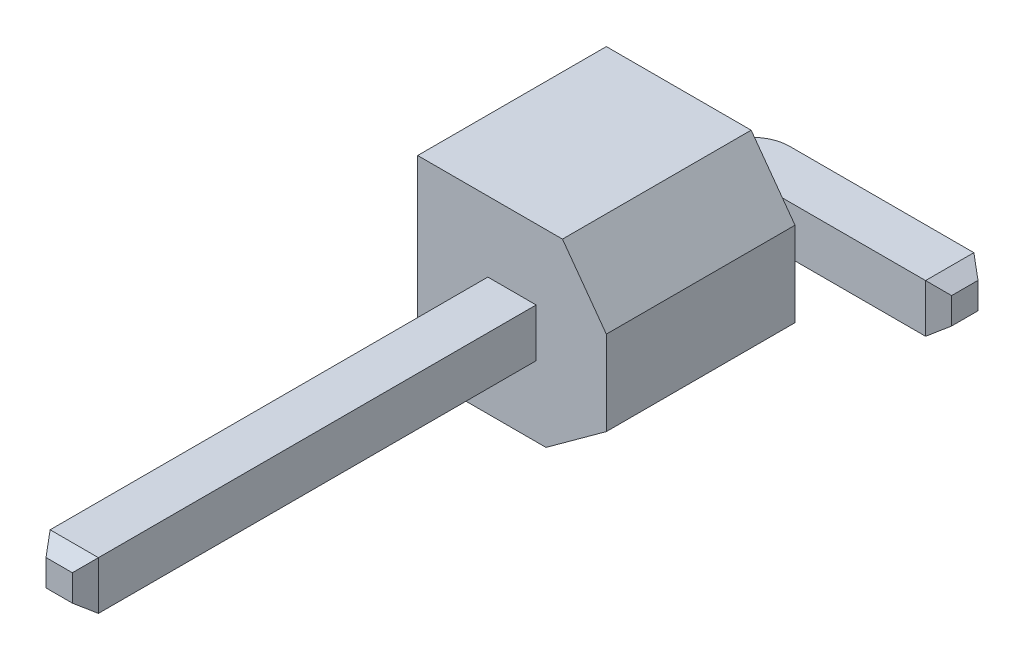
SolidWorks part; units mm, degrees
other "Детальный элемент1"
ref_plane "Спереди" through (0, 0, 0) normal (0, 0, 1) x (1, 0, 0)
ref_plane "Сверху" through (0, 0, 0) normal (0, 1, 0) x (1, 0, 0)
ref_plane "Справа" through (0, 0, 0) normal (1, 0, 0) x (0, 0, -1)
ref_plane "Плоскость1" through (0, 0, 1) normal (0, 0, 1) x (1, 0, 0)
sketch "Эскиз1" plane through (0, 0, 1) normal (0, 0, 1) x (1, 0, 0)
  line L1 (-1.25, -1.25) -> (1.25, -1.25)
  line L2 (-1.25, -1.25) -> (-1.25, 1.25)
  line L3 (-1.25, 1.25) -> (1.25, 1.25)
  line L4 (1.25, -1.25) -> (1.25, 1.25)
  line L5 (-1.25, -1.25) -> (1.25, 1.25) construction
  line L6 (-1.25, 1.25) -> (1.25, -1.25) construction
  point P0 (0, 0)
  dimension "D1" = 2.5
extrude "Бобышка-Вытянуть1" add sketch "Эскиз1" along normal blind 2.5
sketch "Эскиз2" plane through (0, 0, 3.5) normal (0, 0, 1) x (1, 0, 0)
  line L1 (-0.32, 0.32) -> (0.32, 0.32)
  line L2 (-0.32, 0.32) -> (-0.32, -0.32)
  line L3 (-0.32, -0.32) -> (0.32, -0.32)
  line L4 (0.32, 0.32) -> (0.32, -0.32)
  line L5 (-0.32, 0.32) -> (0.32, -0.32) construction
  line L6 (-0.32, -0.32) -> (0.32, 0.32) construction
  point P0 (0, 0)
  dimension "D1" = 0.64
extrude "Бобышка-Вытянуть2" add sketch "Эскиз2" along normal blind 6 and the other way up to surface (3.5 mm away) other way up to plane "Спереди"
sketch "Эскиз4" plane through (0.32, 0, 0) normal (1, 0, 0) x (0, 0, -1)
  line L0 (0, 0.32) -> (-1, 0.32) construction
  line L1 (0, -0.32) -> (-0.64, -0.32)
  line L2 (0, -0.32) -> (0, 0.32)
  line L3 (0, 0.32) -> (-0.64, 0.32)
  line L4 (-0.64, -0.32) -> (-0.64, 0.32)
extrude "Бобышка-Вытянуть4" add sketch "Эскиз4" along normal blind 2.5
fillet "Скругление1" radius 0.5 1 edges at (-0.32, 0, 0)
chamfer "Фаска1" distance 0.2 angle 36 8 edges at (0, 0.32, 9.5) (-0.32, 0, 9.5) (0, -0.32, 9.5) (0.32, 0, 9.5) (2.82, 0.32, 0.32) (2.82, 0, 0) (2.82, -0.32, 0.32) (2.82, 0, 0.64)
chamfer "Фаска2" distance 0.8 angle 36 2 edges at (1.25, 1.25, 2.25) (1.25, -1.25, 2.25)
